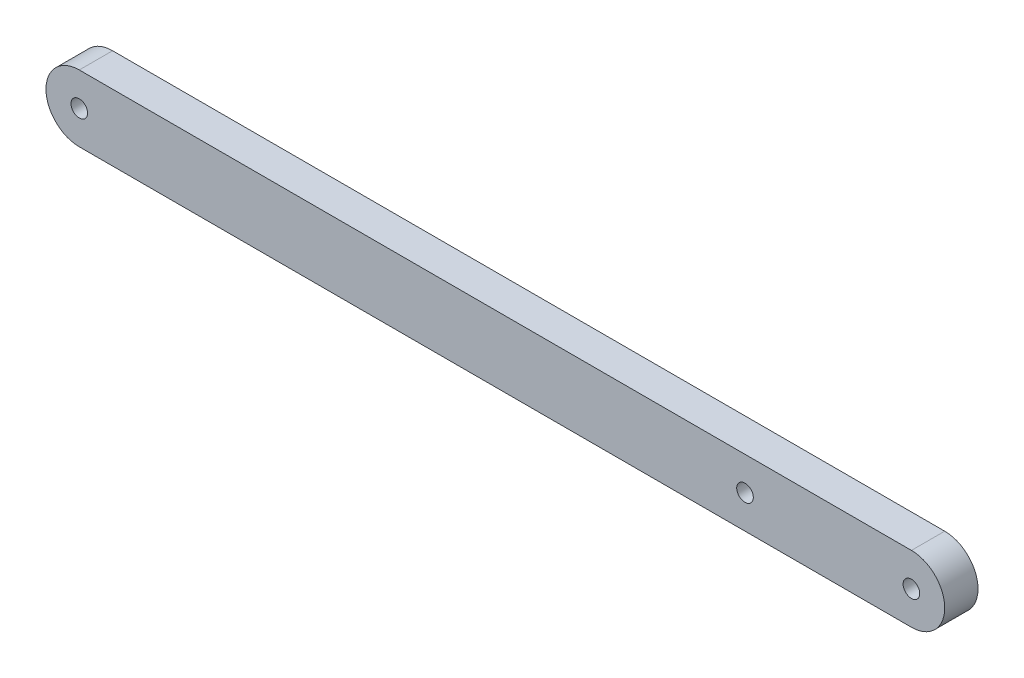
SolidWorks part; units mm, degrees
ref_plane "Front Plane" through (0, 0, 0) normal (0, 0, 1) x (1, 0, 0)
ref_plane "Top Plane" through (0, 0, 0) normal (0, 1, 0) x (1, 0, 0)
ref_plane "Right Plane" through (0, 0, 0) normal (1, 0, 0) x (0, 0, -1)
sketch "Sketch1" plane through (0, 0, 0) normal (0, 0, 1) x (1, 0, 0)
  line L0 (50, 10) -> (-200, 10)
  line L1 (50, -10) -> (-200, -10)
  circle A0 centre (0, 0) radius 2.5
  circle A1 centre (50, 0) radius 2.5
  circle A2 centre (-200, 0) radius 2.5
  arc A3 (-200, 10) -> (-200, -10) centre (-200, 0) ccw
  arc A4 (50, 10) -> (50, -10) centre (50, 0) cw
  dimension "D1" = 5
  dimension "D4" = 10
  dimension "D5" = 10
  dimension "D2" = 50
  dimension "D3" = 200
extrude "Boss-Extrude1" add sketch "Sketch1" along normal blind 10
